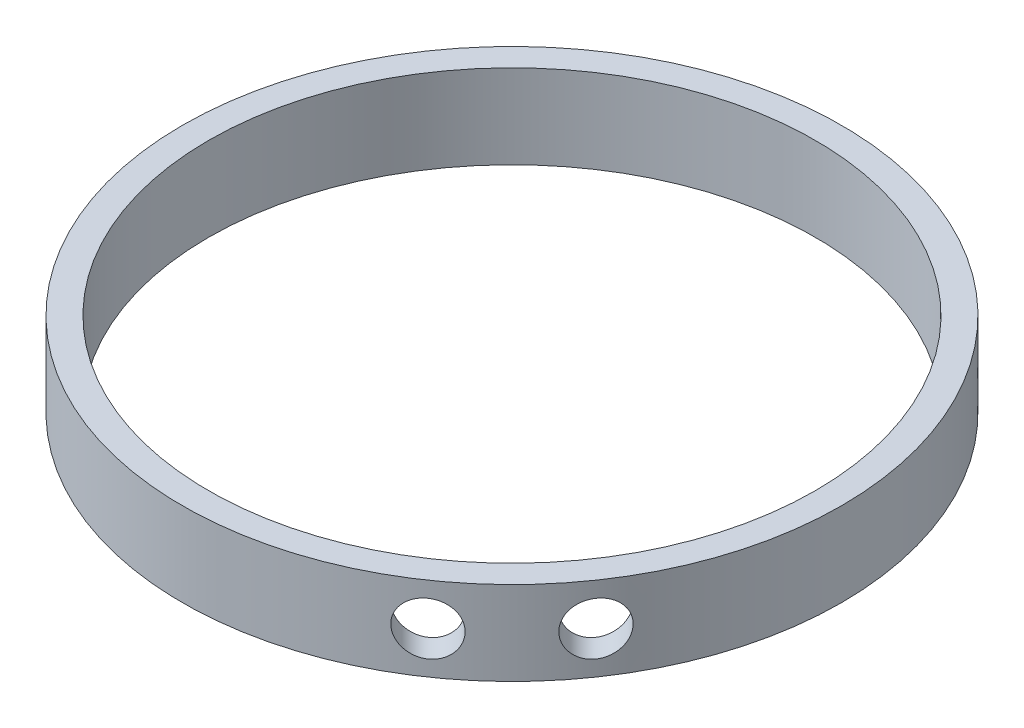
SolidWorks part; units mm, degrees
material "ABS"
ref_plane "Front Plane" through (0, 0, 0) normal (0, 0, 1) x (1, 0, 0)
ref_plane "Top Plane" through (0, 0, 0) normal (0, 1, 0) x (1, 0, 0)
ref_plane "Right Plane" through (0, 0, 0) normal (1, 0, 0) x (0, 0, -1)
sketch "Sketch1" plane through (0, 0, 0) normal (0, 0, 1) x (1, 0, 0)
  line L0 (0, 138.9318) -> (0, -74.0157) construction
  line L1 (44.45, 0) -> (44.45, 204.47)
  line L2 (44.45, 204.47) -> (50.6984, 204.47)
  line L3 (50.6984, 204.47) -> (50.6984, 108.966)
  line L4 (50.6984, 108.966) -> (52.832, 108.966)
  line L5 (52.832, 108.966) -> (52.832, 95.504)
  line L6 (52.832, 95.504) -> (50.6984, 95.504)
  line L7 (50.6984, 95.504) -> (50.6984, 0)
  line L8 (50.6984, 0) -> (44.45, 0)
  dimension "D1" = 88.9
  dimension "D2" = 204.47
  dimension "D3" = 13.462
  dimension "D4" = 101.3968
  dimension "D5" = 105.664
revolve "Revolve1" add sketch "Sketch1" angle 360 about L0
sketch "Sketch2" plane through (0, 204.47, 0) normal (0, 1, 0) x (1, 0, 0)
  circle A0 centre (0, 40.7035) radius 3.7465
  circle A1 centre (0, 0) radius 44.45 construction
  circle A2 centre (0, 40.7035) radius 7.9375
  circle A3 centre (0, 0) radius 50.8 construction
  point P26 (0, 0)
  dimension "D1" = 7.493
  dimension "D2" = 15.875
extrude "Boss-Extrude1" add sketch "Sketch2" against normal up to surface (204.47 mm away) up to face at (-50.6984, 0, 0)
fillet "Fillet1" radius 3.81 2 edges at (-7.2879, 102.235, -43.8485) (7.2879, 102.235, -43.8485)
pattern_circular "CirPattern1" count 4 over 360 about axis through (0, 0, 0) along (0, 1, 0) of "Fillet1", "Boss-Extrude1"
sketch "Sketch3" plane through (0, 204.47, 0) normal (0, 1, 0) x (1, 0, 0)
  circle A1 centre (0, 40.7035) radius 8.636
  dimension "D1" = 17.272
extrude "Cut-Extrude1" cut sketch "Sketch3" against normal blind 12.7
pattern_circular "CirPattern2" count 4 over 360 about axis through (0, 0, 0) along (0, 1, 0) of "Cut-Extrude1"
fillet "Fillet2" radius 2.54 8 edges at (-8.6158, 198.12, -41.2943) (8.6158, 198.12, -41.2943) (41.2943, 198.12, -8.6158) (41.2943, 198.12, 8.6158) (8.6158, 198.12, 41.2943) (-8.6158, 198.12, 41.2943) (-41.2943, 198.12, 8.6158) (-41.2943, 198.12, -8.6158)
ref_plane "Plane1" through (0, 102.235, 0) normal (0, 1, 0) x (1, 0, 0)
mirror "Mirror1" about plane through (0, 102.235, 0) normal (0, 1, 0) of "CirPattern2", "Cut-Extrude1"
fillet "Fillet3" radius 2.54 8 edges at (-41.2943, 6.35, -8.6158) (-41.2943, 6.35, 8.6158) (8.6158, 6.35, 41.2943) (-8.6158, 6.35, 41.2943) (41.2943, 6.35, -8.6158) (41.2943, 6.35, 8.6158) (-8.6158, 6.35, -41.2943) (8.6158, 6.35, -41.2943)
chamfer "Chamfer1" [suppressed] distance 1.27 angle 80
ref_plane "Plane2" through (37.3579, 0, 37.3579) normal (0.7071, 0, 0.7071) x (0, 1, 0)
hole_wizard "5/16 Clearance Hole1" positions "Sketch6" profile "Sketch5" hole size "5/16" standard "ANSI Inch"
sketch "Sketch6" plane through (37.3579, 0, 37.3579) normal (0.7071, 0, 0.7071) x (0, 1, 0)
  line L1 (95.504, 0) -> (108.966, 0)
  line L3 (108.966, -50.6984) -> (108.966, 50.6984) construction
  line L5 (102.235, 9.525) -> (102.235, -9.525)
  line L7 (95.504, 52.832) -> (95.504, -52.832) construction
  point P0 (102.235, -9.525)
  point P2 (102.235, 9.525)
  point P36 (102.235, 0)
  point P40 (102.235, 0)
  point P42 (0, 0)
  point P45 (0, 0)
  dimension "D1" = 19.05
sketch "Sketch5" plane through (44.0931, 102.235, 30.6227) normal (0, 1, 0) x (0.7071, 0, -0.7071)
  line L0 (0, 0) -> (0, 57.3975)
  line L1 (0, 57.3975) -> (4.2164, 54.864)
  line L2 (4.2164, 54.864) -> (4.2164, 0)
  line L5 (4.2164, 0) -> (0, 0)
  line L10 (0, 57.3975) -> (-4.2164, 54.864) construction
  line L11 (0, -6.35) -> (0, 107.95) construction
  dimension "Hole Dia." = 8.4328
  dimension "Hole Depth" = 54.864
  dimension "Drill Angle" = 118
ref_plane "Plane3" through (37.3579, 0, -37.3579) normal (0.7071, 0, -0.7071) x (0, 1, 0)
hole_wizard "#6 Clearance Hole1" positions "Sketch7" profile "Sketch8" hole size "#6" standard "ANSI Inch"
sketch "Sketch7" plane through (37.3579, 0, -37.3579) normal (0.7071, 0, -0.7071) x (0, 1, 0)
  line L2 (95.504, 0) -> (108.966, 0)
  line L4 (108.966, -52.832) -> (108.966, 52.832) construction
  line L5 (95.504, 50.6984) -> (95.504, -50.6984) construction
  point P0 (102.235, 0)
  point P21 (102.235, 0)
  point P22 (0, 0)
  point P25 (0, 0)
sketch "Sketch8" plane through (37.3579, 102.235, -37.3579) normal (0, 1, 0) x (-0.7071, 0, -0.7071)
  line L0 (0, 0) -> (0, 56.0048)
  line L1 (0, 56.0048) -> (1.8986, 54.864)
  line L2 (1.8986, 54.864) -> (1.8986, 0)
  line L5 (1.8986, 0) -> (0, 0)
  line L10 (0, 56.0048) -> (-1.8987, 54.864) construction
  line L11 (0, -6.35) -> (0, 107.95) construction
  dimension "Hole Dia." = 3.7973
  dimension "Hole Depth" = 54.864
  dimension "Drill Angle" = 118
pattern_circular "CirPattern3" [suppressed] count 3 every 90
sketch "Sketch9" plane through (0, 204.47, 0) normal (0, 1, 0) x (1, 0, 0)
  circle A0 centre (0, 0) radius 52.832
extrude "Cut-Extrude2" cut sketch "Sketch9" along normal up to surface (95.504 mm away) from surface
sketch "Sketch10" plane through (0, 0, 0) normal (0, 0, 1) x (1, 0, 0)
  line L0 (0, 204.47) -> (0, 95.504) construction
  line L1 (50.6984, 204.47) -> (-50.6984, 204.47) construction
  line L2 (-52.832, 95.504) -> (52.832, 95.504) construction
  line L4 (52.832, 108.966) -> (48.387, 108.966)
  line L5 (52.832, 108.966) -> (52.832, 95.504)
  line L6 (52.832, 95.504) -> (48.387, 95.504)
  line L7 (48.387, 108.966) -> (48.387, 95.504)
  dimension "D1" = 4.445
revolve "Cut-Revolve1" [suppressed] cut sketch "Sketch10" angle 360 about L0
sketch "Sketch11" plane through (0, 0, 0) normal (0, 0, 1) x (1, 0, 0)
  line L0 (-52.832, 95.504) -> (52.832, 95.504) construction
  line L1 (48.641, 95.504) -> (0, 95.504)
  line L2 (48.641, 95.504) -> (48.641, 108.966)
  line L5 (50.6984, 204.47) -> (-50.6984, 204.47) construction
  line L6 (50.6984, 204.47) -> (0, 204.47)
  line L7 (50.6984, 204.47) -> (50.6984, 108.966)
  line L8 (50.6984, 108.966) -> (48.641, 108.966)
  line L10 (0, 95.504) -> (0, 204.47)
  line L11 (50.6984, 108.966) -> (-50.6984, 108.966) construction
  line L12 (7.9239, 204.47) -> (-7.9239, 204.47) construction
  dimension "D1" = 50.6984
  dimension "D2" = 48.641
revolve "Cut-Revolve2" cut sketch "Sketch11" angle 360 about L10
